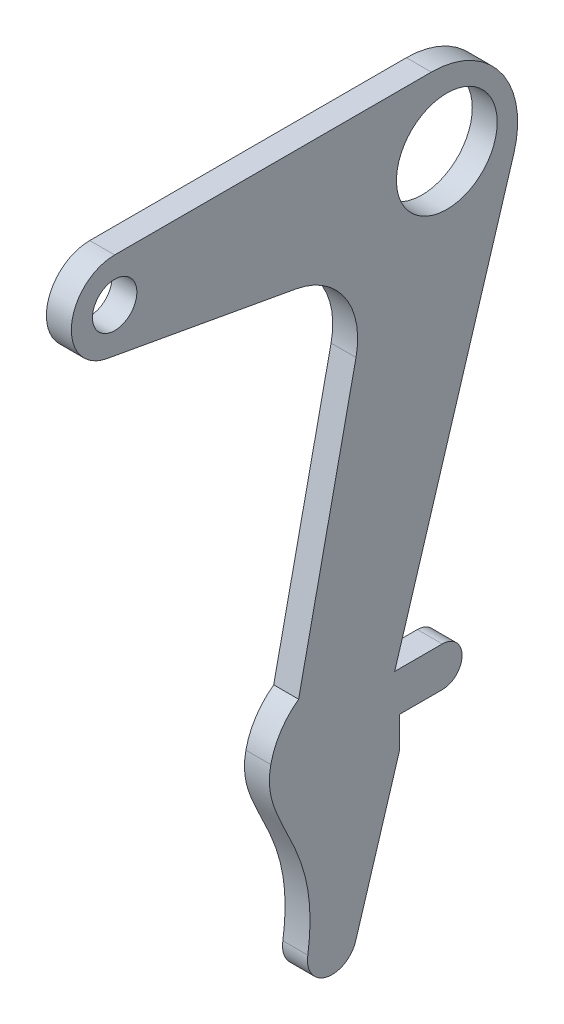
SolidWorks part; units mm, degrees
ref_plane "Front Plane" through (0, 0, 0) normal (0, 0, 1) x (1, 0, 0)
ref_plane "Top Plane" through (0, 0, 0) normal (0, 1, 0) x (1, 0, 0)
ref_plane "Right Plane" through (0, 0, 0) normal (1, 0, 0) x (0, 0, -1)
sketch "Sketch1" plane through (0, 0, 0) normal (1, 0, 0) x (0, 0, -1)
  line L0 (-32.2562, 8.7966) -> (0, 8.7966)
  line L1 (8.4106, -2.577) -> (-3.7319, -42.2066)
  line L2 (-7.6727, -12.5438) -> (-13.5164, -39.7682)
  line L3 (-3.7319, -42.2066) -> (1.1151, -42.2066)
  line L4 (1.1151, -46.2452) -> (-3.2664, -46.2452)
  line L5 (-3.2664, -46.2452) -> (-3.2664, -49.5218)
  line L6 (-33.0418, 0.0405) -> (-13.7666, -3.4462)
  line L7 (-3.2664, -49.5218) -> (-7.7013, -63.9961)
  circle A0 centre (1.5802, 1.0242) radius 5.1308
  arc A1 (0, 8.7966) -> (8.4106, -2.577) centre (0, 0) cw
  arc A2 (-12.5816, -62.8207) -> (-7.7013, -63.9961) centre (-10.1055, -63.2594) ccw
  arc A3 (1.1151, -42.2066) -> (1.1151, -46.2452) centre (1.1151, -44.2259) cw
  arc A4 (-16.3494, -44.1216) -> (-13.5164, -39.7682) centre (-9.2674, -45.6318) cw
  arc A5 (-33.0418, 0.0405) -> (-32.2562, 8.7966) centre (-32.2562, 4.3833) cw
  arc A6 (-13.7666, -3.4462) -> (-7.6727, -12.5438) centre (-15.123, -10.9445) cw
  circle A9 centre (-32.2562, 4.3833) radius 2.262
  spline S0 degree 3 poles (-16.3494, -44.1216) (-17.5282, -49.6499) (-11.0822, -52.6753) (-12.5816, -62.8207) knots 0 0 0 0 1 1 1 1
  dimension "D2" = 7.62
  dimension "D3" = 51.0032
  dimension "D4" = 2.5908
  dimension "D6" = 4.4132
  dimension "D7" = 10.2616
  dimension "D9" = 2.6416
  dimension "D10" = 7.7978
  dimension "D11" = 45.466
  dimension "D12" = 10.0838
  dimension "D13" = 4.0386
  dimension "D15" = 78.105
  dimension "D16" = 6.4008
  dimension "D19" = 7.2412
  dimension "D20" = 2.5146
  dimension "D5" = 48.5648
  dimension "D8" = 12.2428
  dimension "D14" = 24.511
  dimension "D17" = 3.2766
  dimension "D18" = 15.1384
extrude "Boss-Extrude1" add sketch "Sketch1" along normal blind 2.54
